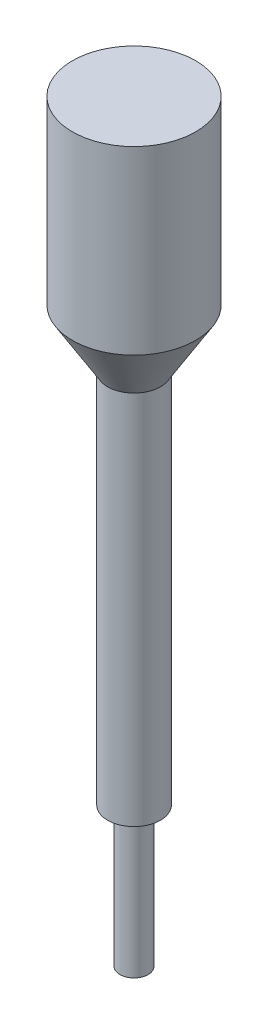
SolidWorks part; units mm, degrees
material "Acero aleado fundido"
ref_plane "Alzado" through (0, 0, 0) normal (1, 0, 0) x (0, 1, 0)
ref_plane "Planta" through (0, 0, 0) normal (0, 0, 1) x (0, 1, 0)
ref_plane "Vista lateral" through (0, 0, 0) normal (0, 1, 0) x (-1, 0, 0)
sketch "Croquis1" plane through (0, 0, 0) normal (1, 0, 0) x (0, 1, 0)
  line L0 (-146.721, 7.5) -> (-146.721, 4)
  line L1 (-146.721, 7.5) -> (-40.121, 7.5)
  line L2 (-40.121, 7.5) -> (-23.721, 17.5)
  line L3 (-23.721, 17.5) -> (27.579, 17.5)
  line L4 (27.579, 17.5) -> (27.579, 0)
  line L5 (50.3342, 0) -> (-199.8422, 0) construction
  line L6 (-146.721, 4) -> (-186.421, 4)
  line L7 (-186.421, 4) -> (-186.421, 0)
  line L8 (-146.721, -4) -> (-186.421, -4) construction
  line L9 (-23.721, -17.5) -> (27.579, -17.5) construction
  line L10 (-40.121, -7.5) -> (-23.721, -17.5) construction
  line L11 (-146.721, -7.5) -> (-40.121, -7.5) construction
  line L12 (-146.721, -7.5) -> (-146.721, -4) construction
  line L13 (-186.421, 0) -> (27.579, 0)
  point P13 (27.579, 0)
  point P14 (-186.421, 0)
  dimension "D1" = 35
  dimension "D2" = 51.3
  dimension "D3" = 16.4
  dimension "D4" = 106.6
  dimension "D5" = 15
  dimension "D6" = 8
  dimension "D7" = 39.7
revolve "Revolución1" add sketch "Croquis1" angle 360 about L13
